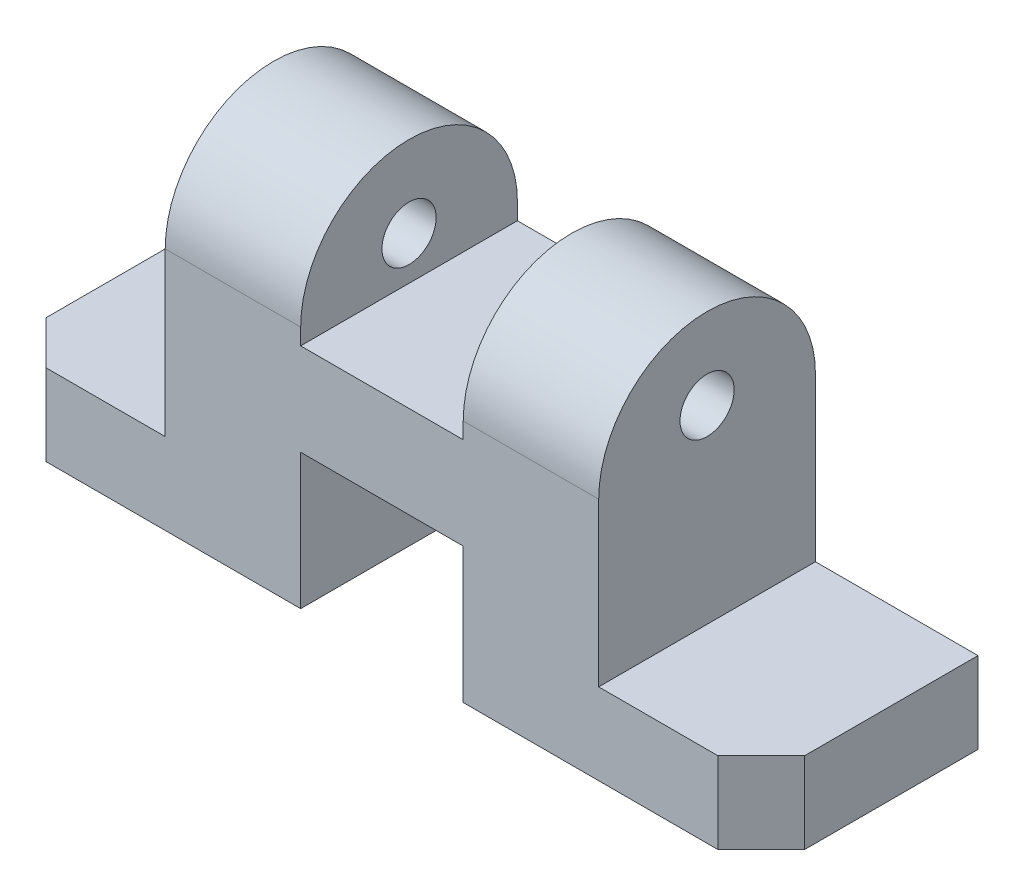
SolidWorks part; units mm, degrees
ref_plane "Front Plane" through (0, 0, 0) normal (0, 0, 1) x (1, 0, 0)
ref_plane "Top Plane" through (0, 0, 0) normal (0, 1, 0) x (1, 0, 0)
ref_plane "Right Plane" through (0, 0, 0) normal (1, 0, 0) x (0, 0, -1)
sketch "Sketch1" plane through (0, 0, 0) normal (0, 0, 1) x (1, 0, 0)
  line L0 (-70, 0) -> (-70, 15)
  line L1 (-70, 15) -> (-40, 15)
  line L2 (-40, 15) -> (-40, 65)
  line L3 (-40, 65) -> (-15, 65)
  line L4 (-15, 65) -> (-15, 42)
  line L5 (0, -55) -> (0, 55) construction
  line L6 (15, 65) -> (15, 42)
  line L7 (40, 65) -> (15, 65)
  line L8 (40, 15) -> (40, 65)
  line L9 (70, 15) -> (40, 15)
  line L10 (70, 0) -> (70, 15)
  line L11 (-15, 42) -> (15, 42)
  line L12 (-70, 0) -> (-15, 0)
  line L13 (-15, 0) -> (-15, 25)
  line L14 (-15, 25) -> (15, 25)
  line L15 (15, 25) -> (15, 0)
  line L16 (15, 0) -> (70, 0)
  line L17 (0, 0) -> (0, 10.6819) construction
  dimension "D1" = 140
  dimension "D2" = 25
  dimension "D3" = 30
  dimension "D4" = 15
  dimension "D5" = 25
  dimension "D6" = 17
  dimension "D7" = 65
extrude "Boss-Extrude1" add sketch "Sketch1" along normal mid plane 40
sketch "Sketch2" plane through (-40, 0, 0) normal (-1, 0, 0) x (0, 0, 1)
  line L1 (-20, 65) -> (-20, 15) construction
  line L2 (20, 65) -> (-20, 65) construction
  line L4 (-20, 65) -> (-20, 45)
  line L5 (0, 65) -> (-20, 65)
  arc A0 (0, 65) -> (-20, 45) centre (0, 45) ccw
  dimension "D1" = 40
  dimension "D2" = 45
extrude "Cut-Extrude1" cut sketch "Sketch2" against normal through all
mirror "Mirror1" about plane through (0, 0, 0) normal (0, 0, 1) of "Cut-Extrude1"
hole_wizard "Hole1" positions "Sketch3" profile "Sketch4" legacy end condition through all
sketch "Sketch3" plane through (40, 0, 0) normal (1, 0, 0) x (0, 0, -1)
  point P0 (0, 50)
  dimension "D1" = 50
sketch "Sketch4" plane through (40, 50, 0) normal (0, 1, 0) x (0, 0, -1)
  line L0 (0, 0) -> (0, 110)
  line L1 (0, 110) -> (5, 110)
  line L2 (5, 110) -> (5, 0)
  line L3 (5, 0) -> (0, 0)
  line L4 (0, 110) -> (0, -10) construction
  dimension "Diameter" = 10
  dimension "Depth" = 110
chamfer "Chamfer1" distance 8 angle 45 2 edges at (-70, 7.5, 20) (70, 7.5, 20)
